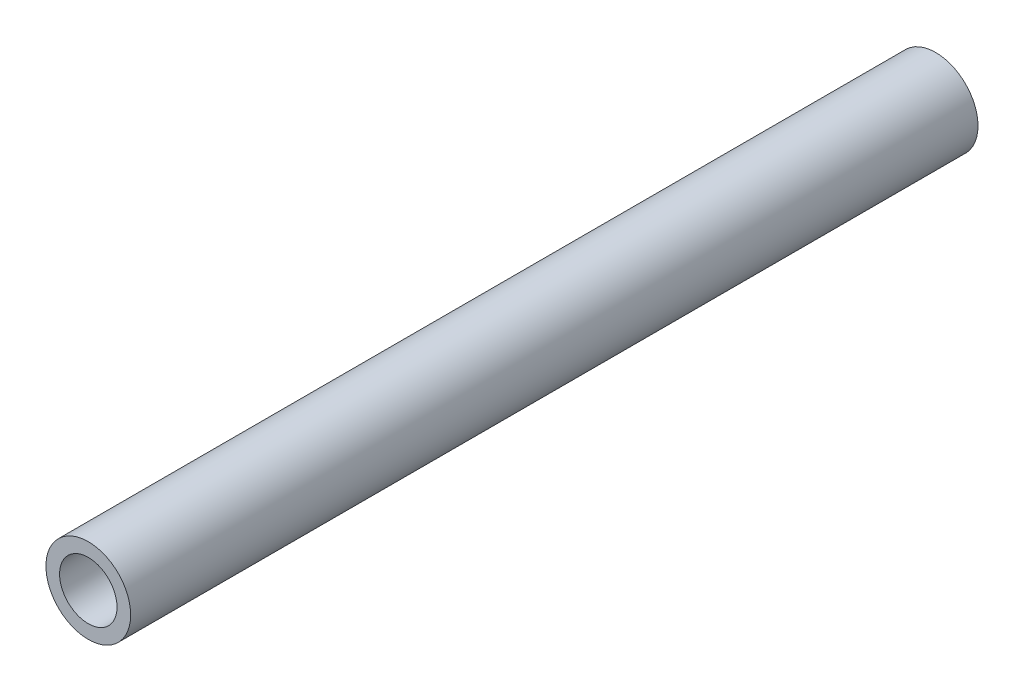
SolidWorks part; units mm, degrees
ref_plane "Front Plane" through (0, 0, 0) normal (0, 0, 1) x (1, 0, 0)
ref_plane "Top Plane" through (0, 0, 0) normal (0, 1, 0) x (1, 0, 0)
ref_plane "Right Plane" through (0, 0, 0) normal (1, 0, 0) x (0, 0, -1)
sketch "Sketch1" plane through (0, 0, 0) normal (0, 0, 1) x (1, 0, 0)
  circle A0 centre (0, 0) radius 2.1526
  circle A1 centre (0, 0) radius 3.175
  dimension "D1" = 6.35
  dimension "D2" = 4.3053
extrude "Boss-Extrude1" add sketch "Sketch1" along normal mid plane 63.5
